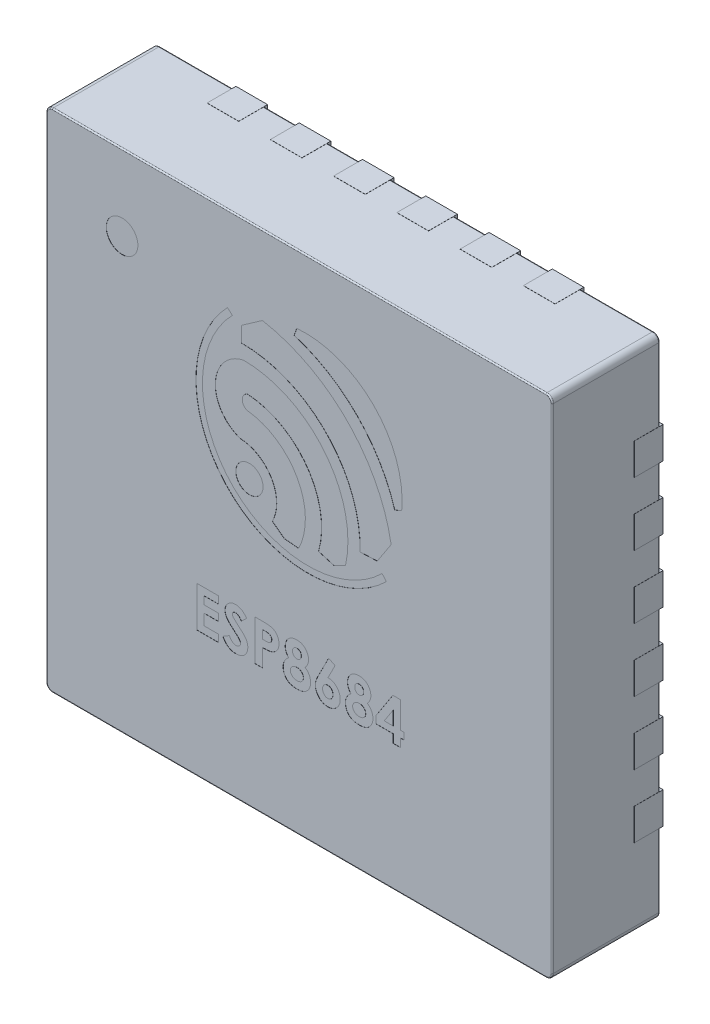
SolidWorks part; units mm, degrees
other "ESP8684-SoC" parameters "D5"=0.3678, "D1"=3.1308, "D2"=3.0402, "D3"=0.4115, "D4"=0.3, "D6"=0.3296, "D7"=0.2637, "D8"=0.9806, "D10"=0.5, "D11"=0.25, "D9"=3
ref_plane "Front Plane" through (0, 0, 0) normal (0, 0, 1) x (1, 0, 0)
ref_plane "Top Plane" through (0, 0, 0) normal (0, 1, 0) x (1, 0, 0)
ref_plane "Right Plane" through (0, 0, 0) normal (1, 0, 0) x (0, 0, -1)
sketch "Sketch1" plane through (0, 0, 0) normal (0, 1, 0) x (1, 0, 0)
  line L1 (-2, -2) -> (2, -2)
  line L2 (-2, -2) -> (-2, 2)
  line L3 (-2, 2) -> (2, 2)
  line L4 (2, -2) -> (2, 2)
  line L5 (-2, -2) -> (2, 2) construction
  line L6 (-2, 2) -> (2, -2) construction
  point P0 (0, 0)
  dimension "D1" = 4
  dimension "D2" = 4
extrude "Boss-Extrude1" add sketch "Sketch1" along normal blind 0.85
fillet "Fillet1" radius 0.05 4 edges at (2, 0.425, -2) (2, 0.425, 2) (-2, 0.425, 2) (-2, 0.425, -2)
fillet "Fillet2" radius 0.01 16 edges at (1.9854, 0.85, 1.9854) (0, 0.85, 2) (-1.9854, 0.85, 1.9854) (-2, 0.85, 0) (-1.9854, 0.85, -1.9854) (0, 0.85, -2) (1.9854, 0.85, -1.9854) (2, 0.85, 0) (2, 0, 0) (1.9854, 0, -1.9854) (0, 0, -2) (1.9854, 0, 1.9854) (0, 0, 2) (-1.9854, 0, 1.9854) (-2, 0, 0) (-1.9854, 0, -1.9854)
sketch "Sketch2" plane through (0, 0, 0) normal (0, -1, 0) x (1, 0, 0)
  line L0 (1.1, 1.4) -> (1.4, 1.1)
  line L1 (-1.35, -1.4) -> (1.35, -1.4)
  line L2 (-1.4, -1.35) -> (-1.4, 1.35)
  line L3 (-1.35, 1.4) -> (1.1, 1.4)
  line L4 (1.4, -1.35) -> (1.4, 1.1)
  line L5 (-1.3854, -1.3854) -> (1.4, 1.4) construction
  line L6 (-1.3854, 1.3854) -> (1.3854, -1.3854) construction
  line L7 (1.1, 1.4) -> (1.4, 1.4) construction
  line L8 (1.4, 1.1) -> (1.4, 1.4) construction
  line L9 (-1.4, 1.4) -> (-1.35, 1.4) construction
  line L10 (-1.4, 1.4) -> (-1.3854, 1.3854) construction
  line L11 (-1.4, 1.35) -> (-1.4, 1.4) construction
  line L12 (-1.4, -1.4) -> (-1.4, -1.35) construction
  line L13 (-1.4, -1.4) -> (-1.3854, -1.3854) construction
  line L14 (-1.4, -1.4) -> (-1.35, -1.4) construction
  line L15 (1.4, -1.4) -> (1.4, -1.35) construction
  line L16 (1.3854, -1.3854) -> (1.4, -1.4) construction
  line L17 (1.35, -1.4) -> (1.4, -1.4) construction
  line L18 (0, -1000) -> (0, 49000) construction
  line L23 (-0.375, 2.001) -> (-0.125, 2.001)
  line L24 (-0.375, 2.001) -> (-0.375, 1.701)
  line L25 (-0.375, 1.701) -> (-0.125, 1.701)
  line L26 (-0.125, 2.001) -> (-0.125, 1.701)
  line L27 (-0.375, 2.001) -> (-0.125, 1.701) construction
  line L28 (-0.375, 1.701) -> (-0.125, 2.001) construction
  line L30 (-0.875, 2.001) -> (-0.875, 1.701)
  line L31 (-0.875, 2.001) -> (-0.625, 2.001)
  line L32 (-0.625, 2.001) -> (-0.625, 1.701)
  line L33 (-0.875, 1.701) -> (-0.625, 1.701)
  line L34 (-0.875, 1.701) -> (-0.625, 2.001) construction
  line L35 (-0.875, 2.001) -> (-0.625, 1.701) construction
  line L36 (-1.375, 2.001) -> (-1.375, 1.701)
  line L37 (-1.375, 2.001) -> (-1.125, 2.001)
  line L38 (-1.125, 2.001) -> (-1.125, 1.701)
  line L39 (-1.375, 1.701) -> (-1.125, 1.701)
  line L40 (-1.375, 1.701) -> (-1.125, 2.001) construction
  line L41 (-1.375, 2.001) -> (-1.125, 1.701) construction
  line L48 (-0.375, 2.001) -> (-0.875, 2.001) construction
  line L162 (-1000, 0) -> (49000, 0) construction
  line L163 (-2, 2) -> (2, 2) construction
  line L164 (0.375, 2.001) -> (0.875, 2.001) construction
  line L167 (1.375, 2.001) -> (1.125, 1.701) construction
  line L168 (1.375, 1.701) -> (1.125, 2.001) construction
  line L169 (0.875, 2.001) -> (0.625, 1.701) construction
  line L170 (0.875, 1.701) -> (0.625, 2.001) construction
  line L171 (0.375, 1.701) -> (0.125, 2.001) construction
  line L172 (0.375, 2.001) -> (0.125, 1.701) construction
  line L177 (1.375, 1.701) -> (1.125, 1.701)
  line L178 (1.125, 2.001) -> (1.125, 1.701)
  line L179 (1.375, 2.001) -> (1.125, 2.001)
  line L180 (1.375, 2.001) -> (1.375, 1.701)
  line L181 (0.875, 1.701) -> (0.625, 1.701)
  line L182 (0.625, 2.001) -> (0.625, 1.701)
  line L183 (0.875, 2.001) -> (0.625, 2.001)
  line L184 (0.875, 2.001) -> (0.875, 1.701)
  line L185 (0.125, 2.001) -> (0.125, 1.701)
  line L186 (0.375, 1.701) -> (0.125, 1.701)
  line L187 (0.375, 2.001) -> (0.375, 1.701)
  line L188 (0.375, 2.001) -> (0.125, 2.001)
  line L189 (0.375, -2.001) -> (0.125, -1.701) construction
  line L190 (0.375, -1.701) -> (0.125, -2.001) construction
  line L191 (0.875, -1.701) -> (0.625, -2.001) construction
  line L192 (0.875, -2.001) -> (0.625, -1.701) construction
  line L193 (1.375, -1.701) -> (1.125, -2.001) construction
  line L194 (1.375, -2.001) -> (1.125, -1.701) construction
  line L197 (0.375, -2.001) -> (0.875, -2.001) construction
  line L198 (-0.375, -2.001) -> (-0.875, -2.001) construction
  line L201 (-1.375, -2.001) -> (-1.125, -1.701) construction
  line L202 (-1.375, -1.701) -> (-1.125, -2.001) construction
  line L203 (-0.875, -2.001) -> (-0.625, -1.701) construction
  line L204 (-0.875, -1.701) -> (-0.625, -2.001) construction
  line L205 (-0.375, -1.701) -> (-0.125, -2.001) construction
  line L206 (-0.375, -2.001) -> (-0.125, -1.701) construction
  line L207 (0.375, -2.001) -> (0.125, -2.001)
  line L208 (0.375, -2.001) -> (0.375, -1.701)
  line L209 (0.375, -1.701) -> (0.125, -1.701)
  line L210 (0.125, -2.001) -> (0.125, -1.701)
  line L211 (0.875, -2.001) -> (0.875, -1.701)
  line L212 (0.875, -2.001) -> (0.625, -2.001)
  line L213 (0.625, -2.001) -> (0.625, -1.701)
  line L214 (0.875, -1.701) -> (0.625, -1.701)
  line L215 (1.375, -2.001) -> (1.375, -1.701)
  line L216 (1.375, -2.001) -> (1.125, -2.001)
  line L217 (1.125, -2.001) -> (1.125, -1.701)
  line L218 (1.375, -1.701) -> (1.125, -1.701)
  line L227 (-1.375, -1.701) -> (-1.125, -1.701)
  line L228 (-1.125, -2.001) -> (-1.125, -1.701)
  line L229 (-1.375, -2.001) -> (-1.125, -2.001)
  line L230 (-1.375, -2.001) -> (-1.375, -1.701)
  line L231 (-0.875, -1.701) -> (-0.625, -1.701)
  line L232 (-0.625, -2.001) -> (-0.625, -1.701)
  line L233 (-0.875, -2.001) -> (-0.625, -2.001)
  line L234 (-0.875, -2.001) -> (-0.875, -1.701)
  line L235 (-0.125, -2.001) -> (-0.125, -1.701)
  line L236 (-0.375, -1.701) -> (-0.125, -1.701)
  line L237 (-0.375, -2.001) -> (-0.375, -1.701)
  line L238 (-0.375, -2.001) -> (-0.125, -2.001)
  line L239 (2.001, 0.375) -> (1.701, 0.125) construction
  line L240 (1.701, 0.375) -> (2.001, 0.125) construction
  line L241 (1.701, 0.875) -> (2.001, 0.625) construction
  line L242 (2.001, 0.875) -> (1.701, 0.625) construction
  line L243 (1.701, 1.375) -> (2.001, 1.125) construction
  line L244 (2.001, 1.375) -> (1.701, 1.125) construction
  line L247 (2.001, 0.375) -> (2.001, 0.875) construction
  line L248 (2.001, -0.375) -> (2.001, -0.875) construction
  line L251 (2.001, -1.375) -> (1.701, -1.125) construction
  line L252 (1.701, -1.375) -> (2.001, -1.125) construction
  line L253 (2.001, -0.875) -> (1.701, -0.625) construction
  line L254 (1.701, -0.875) -> (2.001, -0.625) construction
  line L255 (1.701, -0.375) -> (2.001, -0.125) construction
  line L256 (2.001, -0.375) -> (1.701, -0.125) construction
  line L257 (2.001, 0.375) -> (2.001, 0.125)
  line L258 (2.001, 0.375) -> (1.701, 0.375)
  line L259 (1.701, 0.375) -> (1.701, 0.125)
  line L260 (2.001, 0.125) -> (1.701, 0.125)
  line L261 (2.001, 0.875) -> (1.701, 0.875)
  line L262 (2.001, 0.875) -> (2.001, 0.625)
  line L263 (2.001, 0.625) -> (1.701, 0.625)
  line L264 (1.701, 0.875) -> (1.701, 0.625)
  line L265 (2.001, 1.375) -> (1.701, 1.375)
  line L266 (2.001, 1.375) -> (2.001, 1.125)
  line L267 (2.001, 1.125) -> (1.701, 1.125)
  line L268 (1.701, 1.375) -> (1.701, 1.125)
  line L277 (1.701, -1.375) -> (1.701, -1.125)
  line L278 (2.001, -1.125) -> (1.701, -1.125)
  line L279 (2.001, -1.375) -> (2.001, -1.125)
  line L280 (2.001, -1.375) -> (1.701, -1.375)
  line L281 (1.701, -0.875) -> (1.701, -0.625)
  line L282 (2.001, -0.625) -> (1.701, -0.625)
  line L283 (2.001, -0.875) -> (2.001, -0.625)
  line L284 (2.001, -0.875) -> (1.701, -0.875)
  line L285 (2.001, -0.125) -> (1.701, -0.125)
  line L286 (1.701, -0.375) -> (1.701, -0.125)
  line L287 (2.001, -0.375) -> (1.701, -0.375)
  line L288 (2.001, -0.375) -> (2.001, -0.125)
  line L289 (-2.001, -0.375) -> (-1.701, -0.125) construction
  line L290 (-1.701, -0.375) -> (-2.001, -0.125) construction
  line L291 (-1.701, -0.875) -> (-2.001, -0.625) construction
  line L292 (-2.001, -0.875) -> (-1.701, -0.625) construction
  line L293 (-1.701, -1.375) -> (-2.001, -1.125) construction
  line L294 (-2.001, -1.375) -> (-1.701, -1.125) construction
  line L297 (-2.001, -0.375) -> (-2.001, -0.875) construction
  line L298 (-2.001, 0.375) -> (-2.001, 0.875) construction
  line L301 (-2.001, 1.375) -> (-1.701, 1.125) construction
  line L302 (-1.701, 1.375) -> (-2.001, 1.125) construction
  line L303 (-2.001, 0.875) -> (-1.701, 0.625) construction
  line L304 (-1.701, 0.875) -> (-2.001, 0.625) construction
  line L305 (-1.701, 0.375) -> (-2.001, 0.125) construction
  line L306 (-2.001, 0.375) -> (-1.701, 0.125) construction
  line L307 (-2.001, -0.375) -> (-2.001, -0.125)
  line L308 (-2.001, -0.375) -> (-1.701, -0.375)
  line L309 (-1.701, -0.375) -> (-1.701, -0.125)
  line L310 (-2.001, -0.125) -> (-1.701, -0.125)
  line L311 (-2.001, -0.875) -> (-1.701, -0.875)
  line L312 (-2.001, -0.875) -> (-2.001, -0.625)
  line L313 (-2.001, -0.625) -> (-1.701, -0.625)
  line L314 (-1.701, -0.875) -> (-1.701, -0.625)
  line L315 (-2.001, -1.375) -> (-1.701, -1.375)
  line L316 (-2.001, -1.375) -> (-2.001, -1.125)
  line L317 (-2.001, -1.125) -> (-1.701, -1.125)
  line L318 (-1.701, -1.375) -> (-1.701, -1.125)
  line L327 (-1.701, 1.375) -> (-1.701, 1.125)
  line L328 (-2.001, 1.125) -> (-1.701, 1.125)
  line L329 (-2.001, 1.375) -> (-2.001, 1.125)
  line L330 (-2.001, 1.375) -> (-1.701, 1.375)
  line L331 (-1.701, 0.875) -> (-1.701, 0.625)
  line L332 (-2.001, 0.625) -> (-1.701, 0.625)
  line L333 (-2.001, 0.875) -> (-2.001, 0.625)
  line L334 (-2.001, 0.875) -> (-1.701, 0.875)
  line L335 (-2.001, 0.125) -> (-1.701, 0.125)
  line L336 (-1.701, 0.375) -> (-1.701, 0.125)
  line L337 (-2.001, 0.375) -> (-1.701, 0.375)
  line L338 (-2.001, 0.375) -> (-2.001, 0.125)
  arc A0 (-1.35, 1.4) -> (-1.4, 1.35) centre (-1.35, 1.35) ccw
  arc A1 (-1.4, -1.35) -> (-1.35, -1.4) centre (-1.35, -1.35) ccw
  arc A2 (1.35, -1.4) -> (1.4, -1.35) centre (1.35, -1.35) ccw
  point P0 (0, 0)
  point P12 (-0.25, 1.851)
  point P60 (0.25, 1.851)
  point P93 (0.25, -1.851)
  point P94 (-0.25, -1.851)
  point P127 (1.851, 0.25)
  point P128 (1.851, -0.25)
  point P161 (-1.851, -0.25)
  point P162 (-1.851, 0.25)
  dimension "D5" = 0.1
  dimension "D1" = 2.8
  dimension "D2" = 2.8
  dimension "D4" = 45
  dimension "D6" = 0.3
  dimension "D7" = 0.25
  dimension "D8" = 0.25
  dimension "D11" = 0.001
  dimension "D3" = 0.3
extrude "Boss-Extrude2" add sketch "Sketch2" along normal blind 0.025 and the other way blind 0.203
sketch "Sketch3" plane through (0, 0.85, 0) normal (0, 1, 0) x (1, 0, 0)
  line L7 (-2, 1) -> (2, 1) construction
  line L8 (-2, 2) -> (-2, -2) construction
  line L9 (-0.7548, -0.6028) -> (-0.8101, -0.6263)
  line L11 (2, 1.95) -> (2, -1.95) construction
  line L12 (1.95, -2) -> (-1.95, -2) construction
  line L13 (0.0192, -1.4599) -> (0.0402, -1.4012)
  line L14 (-0.4805, -0.1789) -> (-0.6166, -0.1847)
  line L15 (-0.6166, -0.1847) -> (-0.7266, -0.3527)
  line L16 (0.2909, -1.3779) -> (0.456, -1.262)
  line L17 (0.456, -1.262) -> (0.456, -1.1403)
  line L18 (0.5283, -1.2944) -> (0.5668, -1.3285)
  line L19 (-0.6892, -0.0804) -> (-0.6549, -0.1187)
  line L20 (0.2128, -0.0428) -> (0.1181, 0.0288)
  line L21 (0.1181, 0.0288) -> (0.0043, 0.0388)
  line L22 (-0.1526, -0.0192) -> (-0.2728, 0.0166)
  line L23 (-0.2728, 0.0166) -> (-0.3664, -0.0303)
  line L24 (0, 0) -> (0, 2) construction
  line L25 (-1.95, 2) -> (1.95, 2) construction
  arc A10 (-0.7548, -0.6028) -> (0.0402, -1.4012) centre (0.3934, -0.2544) ccw
  circle A12 centre (1.4, -1.4) radius 0.125
  arc A13 (-0.7266, -0.3527) -> (0.2909, -1.3779) centre (0.5149, -0.138) ccw
  arc A14 (0.4422, -1.0317) -> (0.4658, -0.4821) centre (0.3778, -0.7537) ccw
  arc A15 (0.5668, -1.3285) -> (-0.6892, -0.0804) centre (-0.0693, -0.7126) ccw
  circle A16 centre (0.3935, -0.2411) radius 0.1075
  arc A17 (-0.1526, -0.0192) -> (0.4078, -0.8145) centre (0.4474, -0.1915) ccw
  arc A18 (0.2128, -0.0428) -> (0.4658, -0.4821) centre (0.4786, -0.1822) ccw
  arc A19 (0.0043, 0.0388) -> (0.4099, -0.7016) centre (0.4671, -0.189) ccw
  arc A20 (-0.3664, -0.0303) -> (0.4422, -1.0317) centre (0.4425, -0.2043) ccw
  arc A21 (0.5283, -1.2944) -> (-0.6549, -0.1187) centre (-0.0693, -0.7126) ccw
  arc A22 (-0.4805, -0.1789) -> (0.456, -1.1403) centre (0.4551, -0.2044) ccw
  arc A23 (0.4099, -0.7016) -> (0.4078, -0.8145) centre (0.3909, -0.7577) cw
  arc A24 (-0.8101, -0.6263) -> (0.0192, -1.4599) centre (-0.0444, -0.6939) ccw
  text T0 "ESP8684" font "Century Gothic" height 0.32
  point P0 (0, 1)
  point P52 (0, 0)
  dimension "D2" = 0.25
  dimension "D3" = 0.6
  dimension "D4" = 0.6
extrude "Cut-Extrude1" cut sketch "Sketch3" against normal blind 0.001
move or copy body "Body-Move/Copy1" bodies to move or copy 131 copy no rotation origin (0, 0, 0) rotation axis (0, 0.7071, 0.7071) rotation angle 180
move or copy body "Body-Move/Copy2" bodies to move or copy 132 copy no translate (0, 0, 0.025)
equation "\"D8@Sketch2\"=\"D10@Sketch2\"/2"
equation "\"D1@Sketch1\"=\"D2@Sketch1\""
equation "\"D4@Sketch3\"=\"D3@Sketch3\""
equation "\"D1@Sketch2\"=\"D2@Sketch2\""
